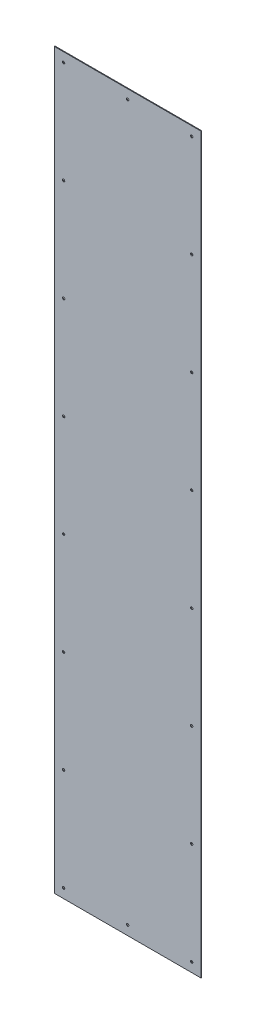
SolidWorks part; units mm, degrees
ref_plane "Alzado" through (0, 0, 0) normal (0, 0, 1) x (1, 0, 0)
ref_plane "Planta" through (0, 0, 0) normal (0, 1, 0) x (1, 0, 0)
ref_plane "Vista lateral" through (0, 0, 0) normal (1, 0, 0) x (0, 0, -1)
sketch "Croquis1" plane through (0, 0, 0) normal (0, 0, 1) x (1, 0, 0)
  line L1 (-200, 1000) -> (200, 1000)
  line L2 (-200, 1000) -> (-200, -1000)
  line L3 (-200, -1000) -> (200, -1000)
  line L4 (200, 1000) -> (200, -1000)
  line L5 (-200, 1000) -> (200, -1000) construction
  line L6 (-200, -1000) -> (200, 1000) construction
  point P0 (0, 0)
  dimension "D1" = 2000
  dimension "D2" = 400
extrude "Saliente-Extruir1" add sketch "Croquis1" along normal blind 1.9
sketch "Croquis2" plane through (0, 0, 1.9) normal (0, 0, 1) x (1, 0, 0)
  line L0 (200, 1000) -> (-200, 1000) construction
  line L1 (-174.6, -974.6) -> (174.6, -974.6) construction
  line L2 (-174.6, -974.6) -> (-174.6, 974.6) construction
  line L3 (-174.6, 974.6) -> (174.6, 974.6) construction
  line L4 (174.6, -974.6) -> (174.6, 974.6) construction
  line L5 (-174.6, -974.6) -> (174.6, 974.6) construction
  line L6 (-174.6, 974.6) -> (174.6, -974.6) construction
  line L7 (-200, 1000) -> (-200, -1000) construction
  line L8 (-174.6, 0) -> (0, 0) construction
  line L9 (0, 0) -> (0, 974.6) construction
  circle A0 centre (-174.6, 974.6) radius 3.175
  circle A1 centre (0, 974.6) radius 3.175
  circle A2 centre (174.6, 974.6) radius 3.175
  circle A3 centre (174.6, -974.6) radius 3.175
  circle A4 centre (0, -974.6) radius 3.175
  circle A5 centre (-174.6, -974.6) radius 3.175
  circle A6 centre (-174.6, 696.15) radius 3.175
  circle A7 centre (-174.6, 417.7) radius 3.175
  circle A8 centre (-174.6, 139.25) radius 3.175
  circle A9 centre (-174.6, -139.2) radius 3.175
  circle A10 centre (-174.6, -417.65) radius 3.175
  circle A11 centre (-174.6, -696.1) radius 3.175
  circle A12 centre (174.6, -696.1) radius 3.175
  circle A13 centre (174.6, -417.65) radius 3.175
  circle A14 centre (174.6, -139.2) radius 3.175
  circle A15 centre (174.6, 139.25) radius 3.175
  circle A16 centre (174.6, 417.7) radius 3.175
  circle A17 centre (174.6, 696.15) radius 3.175
  circle A18 centre (174.6, 974.6) radius 3.175
  point P0 (0, 0)
  dimension "D3" = 6.35
  dimension "D4" = 6.35
  dimension "D5" = 6.35
  dimension "D6" = 7
  dimension "D1" = 25.4
  dimension "D2" = 25.4
extrude "Cortar-Extruir2" cut sketch "Croquis2" against normal blind 10 contours A0 | A1 | A2 | A6 | A7 | A8 | A9 | A10 | A11 | A5 | A4 | A3 | A12 | A13 | A14 | A15 | A16 | A17
